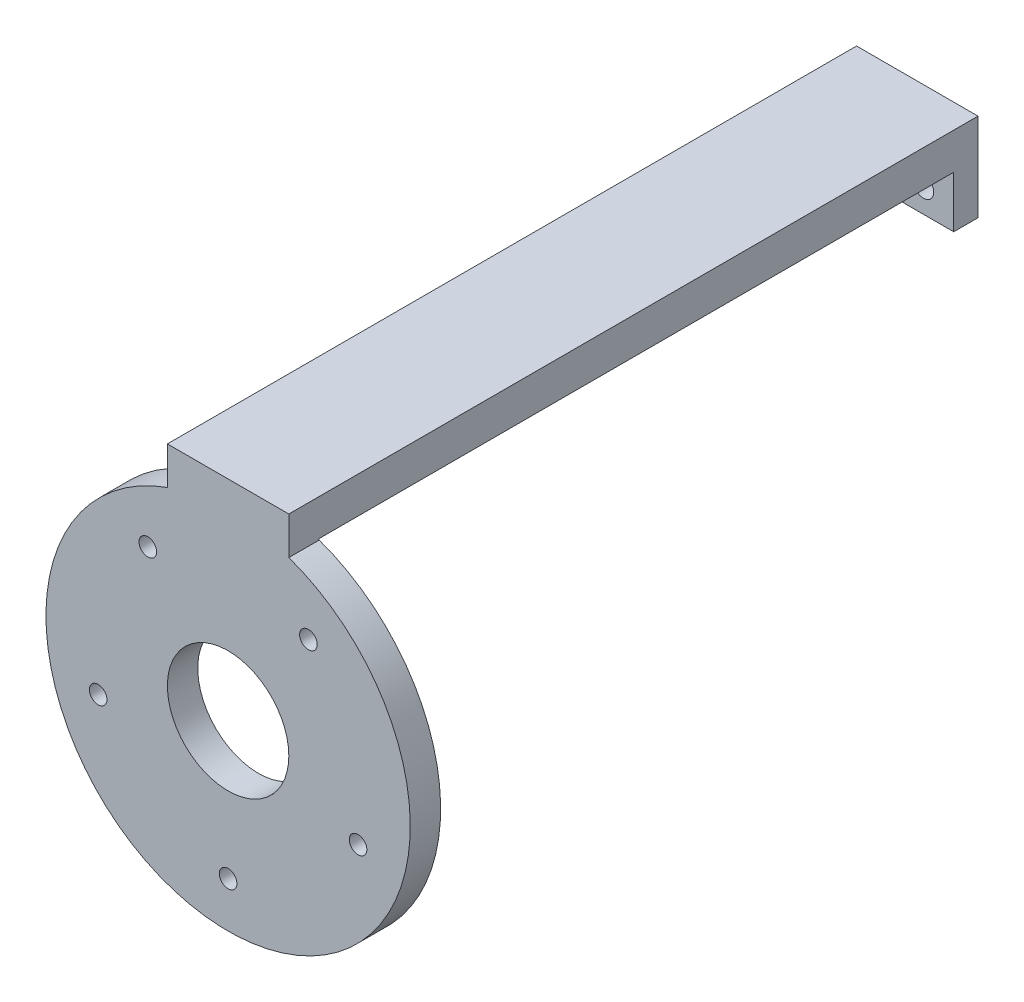
SolidWorks part; units mm, degrees
ref_plane "Front Plane" through (0, 0, 0) normal (0, 0, 1) x (1, 0, 0)
ref_plane "Top Plane" through (0, 0, 0) normal (0, 1, 0) x (1, 0, 0)
ref_plane "Right Plane" through (0, 0, 0) normal (1, 0, 0) x (0, 0, -1)
ref_plane "Plane1" through (0, 0, 384.5) normal (0, 0, 1) x (1, 0, 0)
sketch "Sketch1" plane through (0, 0, 384.5) normal (0, 0, 1) x (1, 0, 0)
  circle A0 centre (300, 300) radius 30
  circle A1 centre (300, 300) radius 10
  circle A2 centre (286.7748, 318.2029) radius 1.45
  circle A3 centre (278.6012, 293.0471) radius 1.45
  circle A4 centre (300, 277.5) radius 1.45
  circle A5 centre (321.3988, 293.0471) radius 1.45
  circle A6 centre (313.2252, 318.2029) radius 1.45
extrude "Boss-Extrude1" add sketch "Sketch1" along normal blind 5
sketch "Sketch2" plane through (0, 0, 384.5) normal (0, 0, 1) x (1, 0, 0)
  line L0 (290, 320) -> (310, 320)
  line L1 (310, 320) -> (310, 334.5)
  line L2 (310, 334.5) -> (290, 334.5)
  line L3 (290, 334.5) -> (290, 320)
extrude "Boss-Extrude2" add sketch "Sketch2" along normal blind 5
ref_plane "Plane2" through (0, 328.5, 0) normal (0, 1, 0) x (1, 0, 0)
sketch "Sketch3" plane through (0, 328.5, 0) normal (0, 1, 0) x (1, 0, 0)
  line L0 (290, -276) -> (310, -276)
  line L1 (310, -276) -> (310, -389.5)
  line L2 (310, -389.5) -> (290, -389.5)
  line L3 (290, -389.5) -> (290, -276)
extrude "Boss-Extrude3" add sketch "Sketch3" along normal blind 6
ref_plane "Plane3" through (0, 0, 276) normal (0, 0, 1) x (1, 0, 0)
sketch "Sketch4" plane through (0, 0, 276) normal (0, 0, 1) x (1, 0, 0)
  line L0 (290, 320) -> (310, 320)
  line L1 (310, 320) -> (310, 334.5)
  line L2 (310, 334.5) -> (290, 334.5)
  line L3 (290, 334.5) -> (290, 320)
  circle A0 centre (295, 324) radius 1.7
  circle A1 centre (305, 324) radius 1.7
extrude "Boss-Extrude4" add sketch "Sketch4" along normal blind 4
